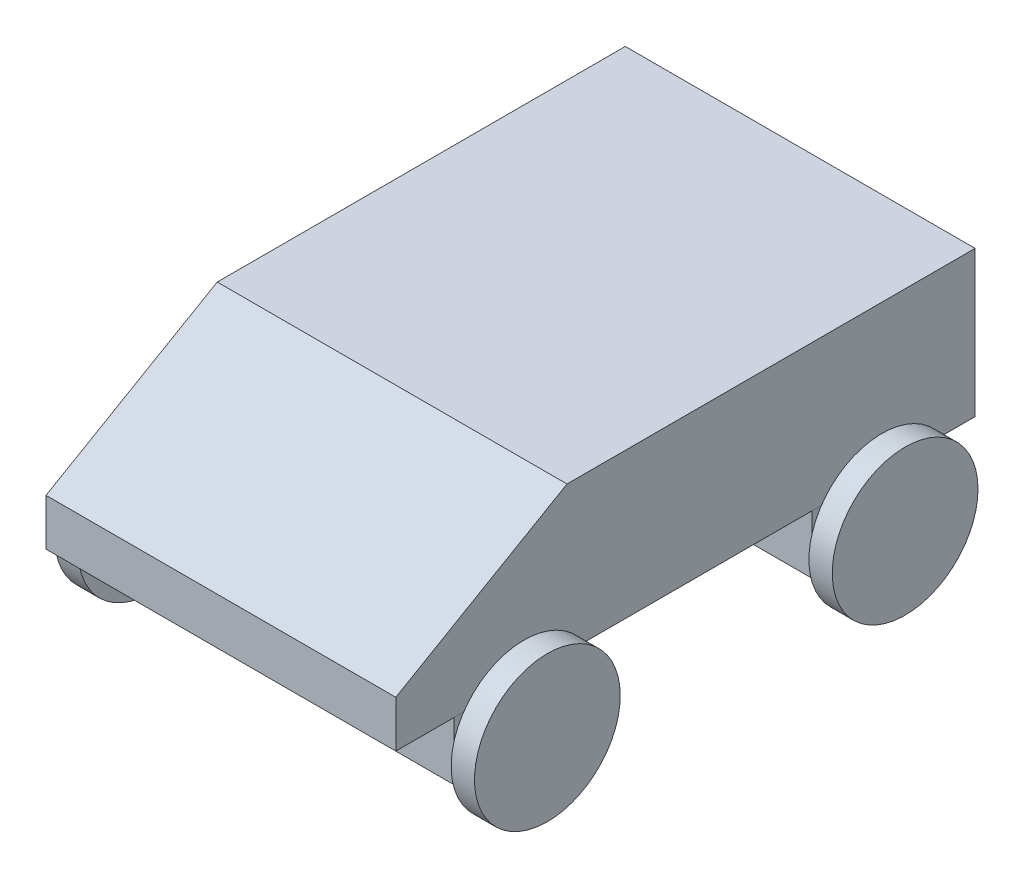
SolidWorks part; units mm, degrees
other "whl3"
other "whl4"
other "mtr4"
other "mtr3"
other "Chassis"
other "mtr1"
other "whl1"
other "mtr2"
other "whl2" parameters "D1"=18.932, "D2"=21.328, "D3"=29.95, "D4"=31.747, "D5"=18.932, "D6"=21.328
ref_plane "Front Plane" through (0, 0, 0) normal (0, 0, 1) x (1, 0, 0)
ref_plane "Top Plane" through (0, 0, 0) normal (0, 1, 0) x (1, 0, 0)
ref_plane "Right Plane" through (0, 0, 0) normal (1, 0, 0) x (0, 0, -1)
sketch "Sketch1" plane through (0, 0, 0) normal (0, 0, 1) x (1, 0, 0)
  line L1 (0, 0) -> (76.2, 0)
  line L2 (0, 0) -> (0, 31.75)
  line L3 (0, 31.75) -> (76.2, 31.75)
  line L4 (76.2, 0) -> (76.2, 31.75)
  dimension "D1" = 76.2
  dimension "D2" = 31.75
extrude "Boss-Extrude1" add sketch "Sketch1" along normal blind 50
sketch "Sketch2" plane through (76.2, 0, 0) normal (1, 0, 0) x (0, 0, -1)
  line L0 (-50, 10.16) -> (-12.7, 31.75)
  line L1 (-50, 0) -> (-50, 31.75) construction
  line L2 (-50, 31.75) -> (0, 31.75) construction
  line L3 (-12.7, 31.75) -> (-50, 31.75)
  line L4 (-50, 31.75) -> (-50, 10.16)
  line L5 (-50, 0) -> (0, 0) construction
  dimension "D1" = 10.16
  dimension "D2" = 12.7
extrude "Cut-Extrude1" cut sketch "Sketch2" against normal through all
sketch "Sketch3" plane through (0, 0, 0) normal (0, 0, -1) x (-1, 0, 0)
  line L4 (0, 0) -> (0, 31.75)
  line L5 (0, 31.75) -> (-76.2, 31.75)
  line L6 (-76.2, 31.75) -> (-76.2, 0)
  line L7 (-76.2, 0) -> (0, 0)
  line L8 (0, 0) -> (0, 31.75)
  line L9 (0, 31.75) -> (-76.2, 31.75)
  line L10 (-76.2, 31.75) -> (-76.2, 0)
  line L11 (-76.2, 0) -> (0, 0)
  dimension "D1" = 0
extrude "Boss-Extrude2" add sketch "Sketch3" along normal blind 76.2
sketch "Sketch4" plane through (0, 0, 0) normal (0, -1, 0) x (1, 0, 0)
  line L0 (76.2, 50) -> (76.2, -76.2) construction
  line L1 (76.2, 37.3) -> (57.15, 37.3)
  line L2 (76.2, 37.3) -> (76.2, 11.9)
  line L3 (76.2, 11.9) -> (57.15, 11.9)
  line L4 (57.15, 37.3) -> (57.15, 11.9)
  line L5 (0, 50) -> (76.2, 50) construction
  line L6 (76.2, -40.64) -> (57.15, -40.64)
  line L7 (76.2, -40.64) -> (76.2, -66.04)
  line L8 (76.2, -66.04) -> (57.15, -66.04)
  line L9 (57.15, -40.64) -> (57.15, -66.04)
  line L10 (76.2, -76.2) -> (0, -76.2) construction
  line L11 (38.1, -76.2) -> (38.1, 50) construction
  line L12 (0, 11.9) -> (19.05, 11.9)
  line L13 (19.05, 37.3) -> (19.05, 11.9)
  line L14 (0, 37.3) -> (19.05, 37.3)
  line L15 (0, 37.3) -> (0, 11.9)
  line L16 (0, -66.04) -> (19.05, -66.04)
  line L17 (19.05, -40.64) -> (19.05, -66.04)
  line L18 (0, -40.64) -> (19.05, -40.64)
  line L19 (0, -40.64) -> (0, -66.04)
  dimension "D1" = 12.7
  dimension "D2" = 10.16
  dimension "D3" = 25.4
  dimension "D4" = 25.4
  dimension "D5" = 19.05
  dimension "D6" = 19.05
extrude "Boss-Extrude3" add sketch "Sketch4" along normal blind 12.7 separate body
sketch "Sketch5" plane through (76.2, 0, 0) normal (1, 0, 0) x (0, 0, -1)
  line L0 (-37.3, 0) -> (-11.9, -12.7) construction
  line L1 (40.64, 0) -> (66.04, -12.7) construction
  circle A0 centre (-24.6, -6.35) radius 2.54
  circle A1 centre (53.34, -6.35) radius 2.54
  point P12 (44.1535, -2.7969)
  point P14 (0, 0)
  point P15 (0, 0)
  point P16 (-35.1074, -2.3261)
  point P17 (0, 0)
  dimension "D1" = 5.08
  dimension "D2" = 5.08
extrude "Boss-Extrude4" add sketch "Sketch5" along normal blind 2.54 separate body
sketch "Sketch6" plane through (78.74, 0, 0) normal (1, 0, 0) x (0, 0, -1)
  circle A0 centre (-24.6, -6.35) radius 15.875
  circle A1 centre (53.34, -6.35) radius 15.875
  dimension "D1" = 31.75
  dimension "D2" = 31.75
extrude "Boss-Extrude5" add sketch "Sketch6" along normal blind 5.08
ref_plane "Plane1" through (38.1, 0, 0) normal (1, 0, 0) x (0, 0, -1)
mirror "Mirror1" about plane through (38.1, 0, 0) normal (1, 0, 0) of "Boss-Extrude4", "Boss-Extrude5"
ref_plane "Plane2" through (0, 0, 0) normal (-1, 0, 0) x (0, 0, 1)
split "Split1" trim tools "Plane2" bodies to split 117 118 resulting bodies 122 123 124 125
equation "\"D6@Sketch4\"=\"D5@Sketch4\""
equation "\"D4@Sketch4\"=\"D3@Sketch4\""
equation "\"D2@Sketch5\"=\"D1@Sketch5\""
equation "\"D2@Sketch6\"=\"D1@Sketch6\""
